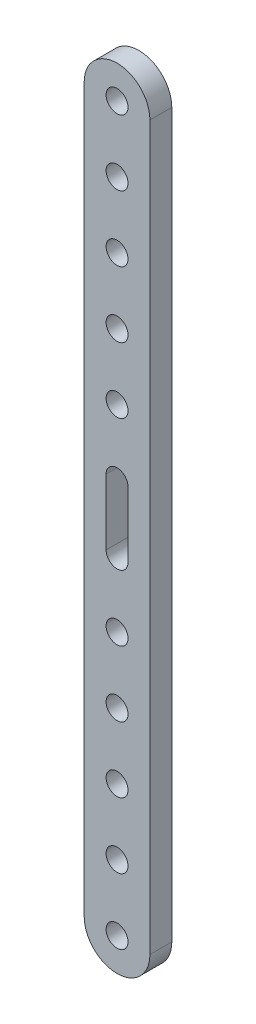
SolidWorks part; units mm, degrees
ref_plane "Alzado" through (0, 0, 0) normal (0, 0, 1) x (1, 0, 0)
ref_plane "Planta" through (0, 0, 0) normal (0, 1, 0) x (1, 0, 0)
ref_plane "Vista lateral" through (0, 0, 0) normal (1, 0, 0) x (0, 0, -1)
sketch "Model" plane through (0, 0, 0) normal (0, 0, 1) x (1, 0, 0)
  line L0 (213.2508, 89.4285) -> (213.2508, 188.4285)
  line L1 (204.2508, 188.4285) -> (204.2508, 89.4285)
  line L2 (207.2508, 134.4285) -> (207.2508, 143.4285)
  line L3 (210.2508, 143.4285) -> (210.2508, 134.4285)
  circle A0 centre (208.7508, 179.4285) radius 1.5
  circle A1 centre (208.7508, 188.4285) radius 1.5
  circle A2 centre (208.7508, 152.4285) radius 1.5
  circle A3 centre (208.7508, 161.4285) radius 1.5
  circle A4 centre (208.7508, 170.4285) radius 1.5
  arc A5 (204.2508, 89.4285) -> (213.2508, 89.4285) centre (208.7508, 89.4285) ccw
  arc A6 (213.2508, 188.4285) -> (204.2508, 188.4285) centre (208.7508, 188.4285) ccw
  circle A7 centre (208.7508, 116.4285) radius 1.5
  circle A8 centre (208.7508, 125.4285) radius 1.5
  circle A9 centre (208.7508, 89.4285) radius 1.5
  circle A10 centre (208.7508, 98.4285) radius 1.5
  circle A11 centre (208.7508, 107.4285) radius 1.5
  arc A12 (207.2508, 134.4285) -> (210.2508, 134.4285) centre (208.7508, 134.4285) ccw
  arc A13 (210.2508, 143.4285) -> (207.2508, 143.4285) centre (208.7508, 143.4285) ccw
extrude "Saliente-Extruir1" add sketch "Model" along normal blind 3
